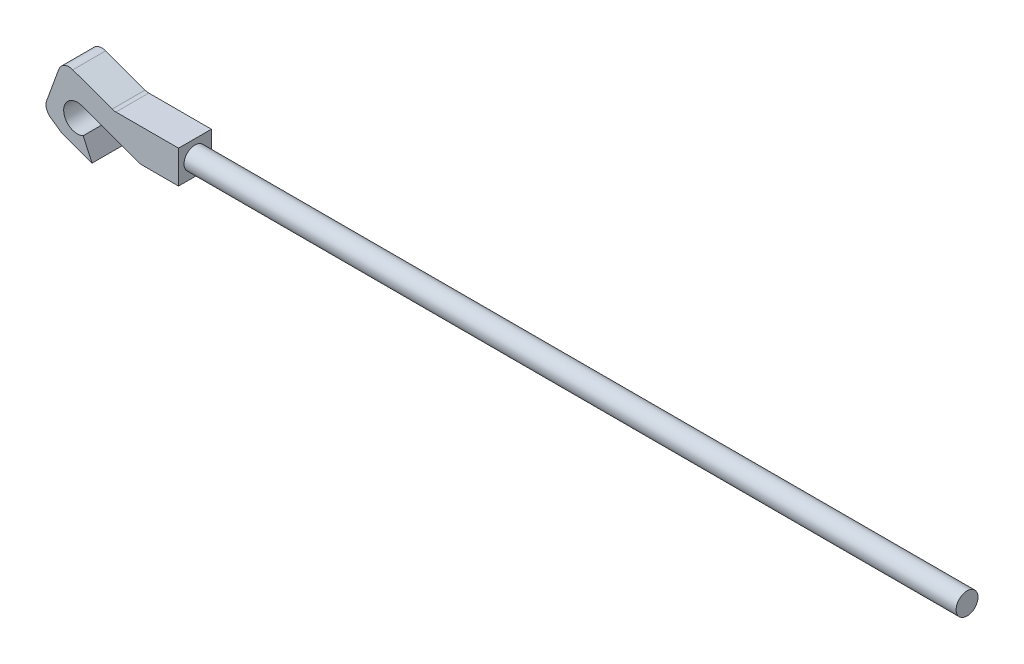
SolidWorks part; units mm, degrees
ref_plane "Front Plane" through (0, 0, 0) normal (0, 0, 1) x (1, 0, 0)
ref_plane "Top Plane" through (0, 0, 0) normal (0, 1, 0) x (1, 0, 0)
ref_plane "Right Plane" through (0, 0, 0) normal (1, 0, 0) x (0, 0, -1)
sketch "Sketch1" plane through (0, 0, 0) normal (1, 0, 0) x (0, 0, -1)
  circle A0 centre (0, 0) radius 25.4
  dimension "D1" = 50.8
extrude "Boss-Extrude1" add sketch "Sketch1" along normal blind 1828.8
sketch "Sketch2" plane through (0, 0, 0) normal (0, 0, 1) x (1, 0, 0)
  line L0 (38.1, -38.1) -> (-46.3213, -38.1)
  line L6 (-107.1498, 38.1) -> (38.1, 38.1)
  line L7 (38.1, 38.1) -> (38.1, -38.1)
  line L8 (-115.8371, 39.6318) -> (-207.1013, 72.8492)
  line L9 (-239.6568, 57.6684) -> (-267.74, -19.4897)
  line L10 (-258.4407, -48.9835) -> (-233.947, -66.1342)
  line L11 (-233.947, -66.1342) -> (-162.3424, -92.1961)
  line L14 (-185.6901, 10.996) -> (-55.0086, -36.5682)
  line L16 (-162.3424, -92.1961) -> (-183.1311, -47.6145)
  line L17 (0, 25.4) -> (0, -25.4) construction
  line L18 (-183.1311, -47.6145) -> (-149.2166, -31.8) construction
  arc A2 (-185.6901, 10.996) -> (-183.1311, -47.6145) centre (-196.5492, -18.8393) ccw
  arc A3 (-207.1013, 72.8492) -> (-239.6568, 57.6684) centre (-215.7886, 48.9811) ccw
  arc A4 (-267.74, -19.4897) -> (-258.4407, -48.9835) centre (-243.8718, -28.177) ccw
  arc A5 (-46.3213, -38.1) -> (-55.0086, -36.5682) centre (-46.3213, -12.7) cw
  arc A6 (-115.8371, 39.6318) -> (-107.1498, 38.1) centre (-107.1498, 63.5) ccw
  point P10 (38.1, 0)
  point P33 (-230.9695, 81.5366)
  point P36 (-274.406, -37.8044)
  point P39 (-50.8, -38.1)
  point P42 (-111.6285, 38.1)
  dimension "D7" = 66.675
  dimension "D8" = 31.75
  dimension "D13" = 25.4
  dimension "D14" = 25.4
  dimension "D1" = 76.2
  dimension "D2" = 38.1
  dimension "D3" = 50.8
  dimension "D4" = 127
  dimension "D5" = 127
  dimension "D6" = 20
  dimension "D9" = 50.8
  dimension "D10" = 45
  dimension "D11" = 15
  dimension "D12" = 76.2
extrude "Boss-Extrude2" add sketch "Sketch2" against normal mid plane 76.2
scale "Scale1" scale about centroid uniform scaling yes scale factor 2
